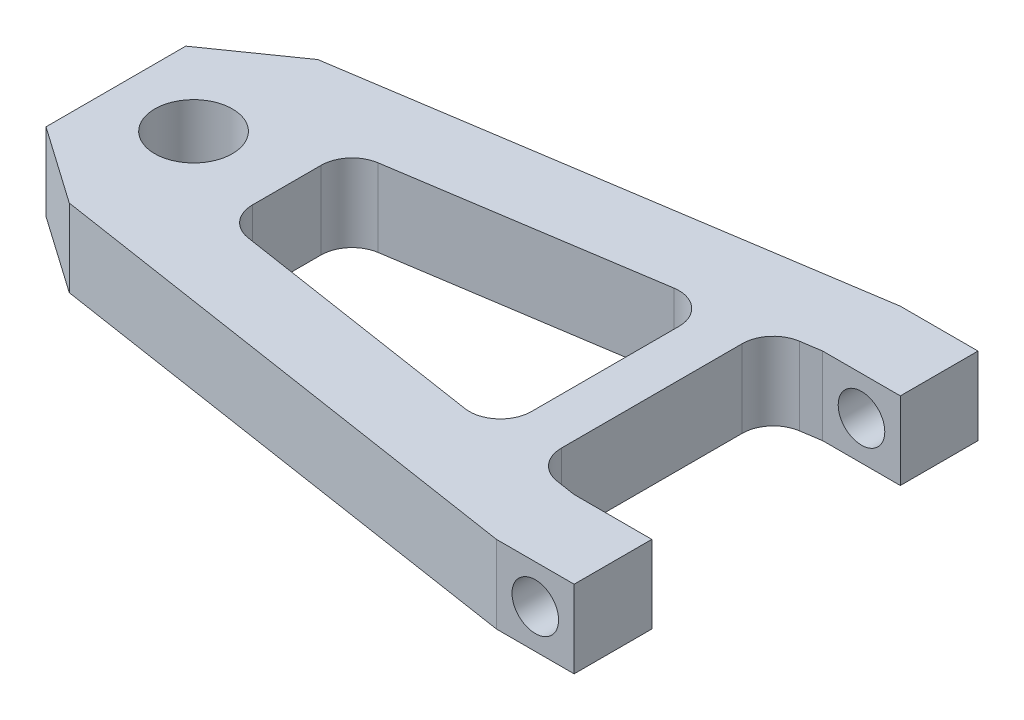
SolidWorks part; units mm, degrees
ref_plane "Front Plane" through (0, 0, 0) normal (0, 0, 1) x (1, 0, 0)
ref_plane "Top Plane" through (0, 0, 0) normal (0, 1, 0) x (1, 0, 0)
ref_plane "Right Plane" through (0, 0, 0) normal (1, 0, 0) x (0, 0, -1)
sketch "Sketch1" plane through (0, 0, 0) normal (0, 1, 0) x (1, 0, 0)
  line L0 (0, 8) -> (-5, 4.499)
  line L1 (-5, 4.499) -> (-5, -4.499)
  line L2 (-12.5835, 0) -> (24.4152, 0) construction
  line L3 (0, 8) -> (32.5, 13)
  line L4 (32.5, 13) -> (37.5, 13)
  line L5 (37.5, 13) -> (37.5, 8)
  line L6 (37.5, 8) -> (32.5, 8)
  line L7 (32.5, 8) -> (31.1959, 7.7994)
  line L8 (6, 2.2072) -> (6, -2.2072)
  line L9 (0, 14.1522) -> (0, -10.7983) construction
  line L10 (35, 11.7616) -> (35, -13.4259) construction
  line L11 (0, -8) -> (-5, -4.499)
  line L12 (0, -8) -> (32.5, -13)
  line L13 (32.5, -13) -> (37.5, -13)
  line L14 (37.5, -13) -> (37.5, -8)
  line L15 (37.5, -8) -> (32.5, -8)
  line L16 (32.5, -8) -> (31.1959, -7.7994)
  line L17 (29.5, 5.8226) -> (29.5, -5.8226)
  line L18 (26.5, 4.7457) -> (26.5, -4.7457)
  line L19 (24.1959, 6.7224) -> (7.6959, 4.184)
  line L20 (24.1959, -6.7224) -> (7.6959, -4.184)
  circle A0 centre (0, 0) radius 2.5
  arc A1 (6, 2.2072) -> (7.6959, 4.184) centre (8, 2.2072) cw
  arc A2 (6, -2.2072) -> (7.6959, -4.184) centre (8, -2.2072) ccw
  arc A3 (31.1959, 7.7994) -> (29.5, 5.8226) centre (31.5, 5.8226) ccw
  arc A4 (29.5, -5.8226) -> (31.1959, -7.7994) centre (31.5, -5.8226) ccw
  arc A5 (26.5, -4.7457) -> (24.1959, -6.7224) centre (24.5, -4.7457) cw
  arc A6 (26.5, 4.7457) -> (24.1959, 6.7224) centre (24.5, 4.7457) ccw
  point P24 (-5, 0)
  point P32 (6, 0)
  point P39 (26.5, -7.0769)
  point P42 (26.5, 7.0769)
  dimension "D1" = 5
  dimension "D6" = 2
  dimension "D13" = 2
  dimension "D2" = 5
  dimension "D3" = 5
  dimension "D4" = 5
  dimension "D5" = 6
  dimension "D7" = 35
  dimension "D8" = 16
  dimension "D9" = 16
  dimension "D10" = 55
  dimension "D11" = 3
  dimension "D12" = 3
extrude "Boss-Extrude1" add sketch "Sketch1" along normal blind 5
sketch "Sketch2" plane through (0, 0, 13) normal (0, 0, 1) x (1, 0, 0)
  line L0 (32.5, 5) -> (37.5, 0) construction
  circle A0 centre (35, 2.5) radius 1.5
  point P6 (0, 0)
  point P7 (0, 0)
  point P8 (0, 0)
  dimension "D1" = 3
extrude "Cut-Extrude1" cut sketch "Sketch2" against normal through all
